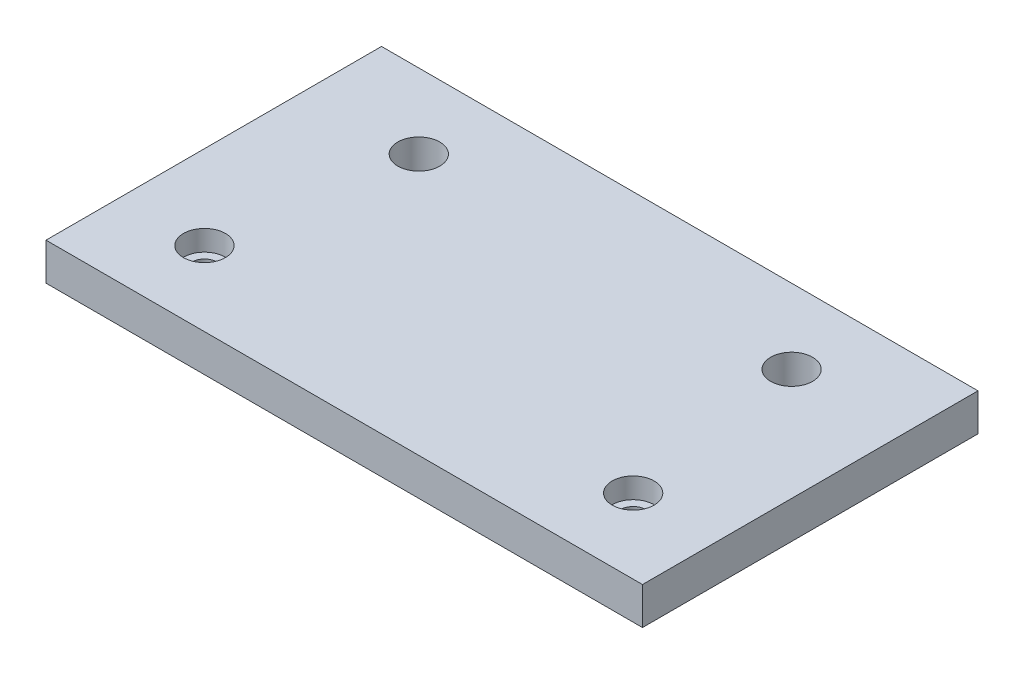
SolidWorks part; units mm, degrees
ref_plane "Front Plane" through (0, 0, 0) normal (0, 0, 1) x (1, 0, 0)
ref_plane "Top Plane" through (0, 0, 0) normal (0, 1, 0) x (1, 0, 0)
ref_plane "Right Plane" through (0, 0, 0) normal (1, 0, 0) x (0, 0, -1)
sketch "Sketch1" plane through (0, 0, 0) normal (0, 1, 0) x (1, 0, 0)
  line L1 (0, 0) -> (101.6, 0)
  line L2 (0, 0) -> (0, -57.15)
  line L3 (0, -57.15) -> (101.6, -57.15)
  line L4 (101.6, 0) -> (101.6, -57.15)
  dimension "D1" = 101.6
  dimension "D2" = 57.15
extrude "Boss-Extrude1" add sketch "Sketch1" along normal blind 6.35
sketch "Sketch2" plane through (0, 6.35, 0) normal (0, 1, 0) x (1, 0, 0)
  line L0 (50.8, 0) -> (50.8, -57.15) construction
  line L1 (101.6, 0) -> (0, 0) construction
  line L2 (0, -57.15) -> (101.6, -57.15) construction
  line L3 (0, -28.575) -> (101.6, -28.575) construction
  line L4 (0, 0) -> (0, -57.15) construction
  line L5 (101.6, -57.15) -> (101.6, 0) construction
  point P12 (14.2875, -44.45)
  point P13 (87.3125, -44.45)
  point P14 (19.05, -12.7)
  point P15 (82.55, -12.7)
  dimension "D1" = 36.5125
  dimension "D2" = 12.7
  dimension "D3" = 31.75
  dimension "D4" = 31.75
hole_wizard "CBORE for #6 Socket Head Cap Screw1" positions "Sketch3" profile "Sketch4" counterbore size "#6" standard "ANSI Inch" end condition up to next
sketch "Sketch3" plane through (0, 6.35, 0) normal (0, 1, 0) x (1, 0, 0)
  point P0 (14.2875, -44.45)
  point P3 (87.3125, -44.45)
sketch "Sketch4" plane through (14.2875, 6.35, 44.45) normal (1, 0, 0) x (0, 0, 1)
  line L0 (0, 0) -> (0, 6.35)
  line L1 (0, 6.35) -> (2.1526, 6.35)
  line L3 (2.1526, 6.35) -> (2.1526, 3.5052)
  line L4 (2.1526, 3.5052) -> (3.5725, 3.5052)
  line L5 (3.5725, 3.5052) -> (3.5725, 0)
  line L7 (3.5725, 0) -> (0, 0)
  line L11 (0, -6.35) -> (0, 107.95) construction
  dimension "Thru Hole Dia." = 4.3053
  dimension "Thru Hole Depth" = 6.35
  dimension "C'Bore Dia." = 7.145
  dimension "C'Bore Depth" = 3.5052
hole_wizard "1/4 Clearance Hole1" positions "Sketch5" profile "Sketch6" hole size "1/4" standard "ANSI Inch" end condition up to next
sketch "Sketch5" plane through (0, 6.35, 0) normal (0, 1, 0) x (1, 0, 0)
  point P0 (19.05, -12.7)
  point P3 (82.55, -12.7)
sketch "Sketch6" plane through (19.05, 6.35, 12.7) normal (1, 0, 0) x (0, 0, 1)
  line L0 (0, 0) -> (0, 6.35)
  line L1 (0, 6.35) -> (3.5712, 6.35)
  line L2 (3.5712, 6.35) -> (3.5712, 0)
  line L5 (3.5712, 0) -> (0, 0)
  line L11 (0, -6.35) -> (0, 107.95) construction
  dimension "Thru Hole Dia." = 7.1425
  dimension "Thru Hole Depth" = 6.35
